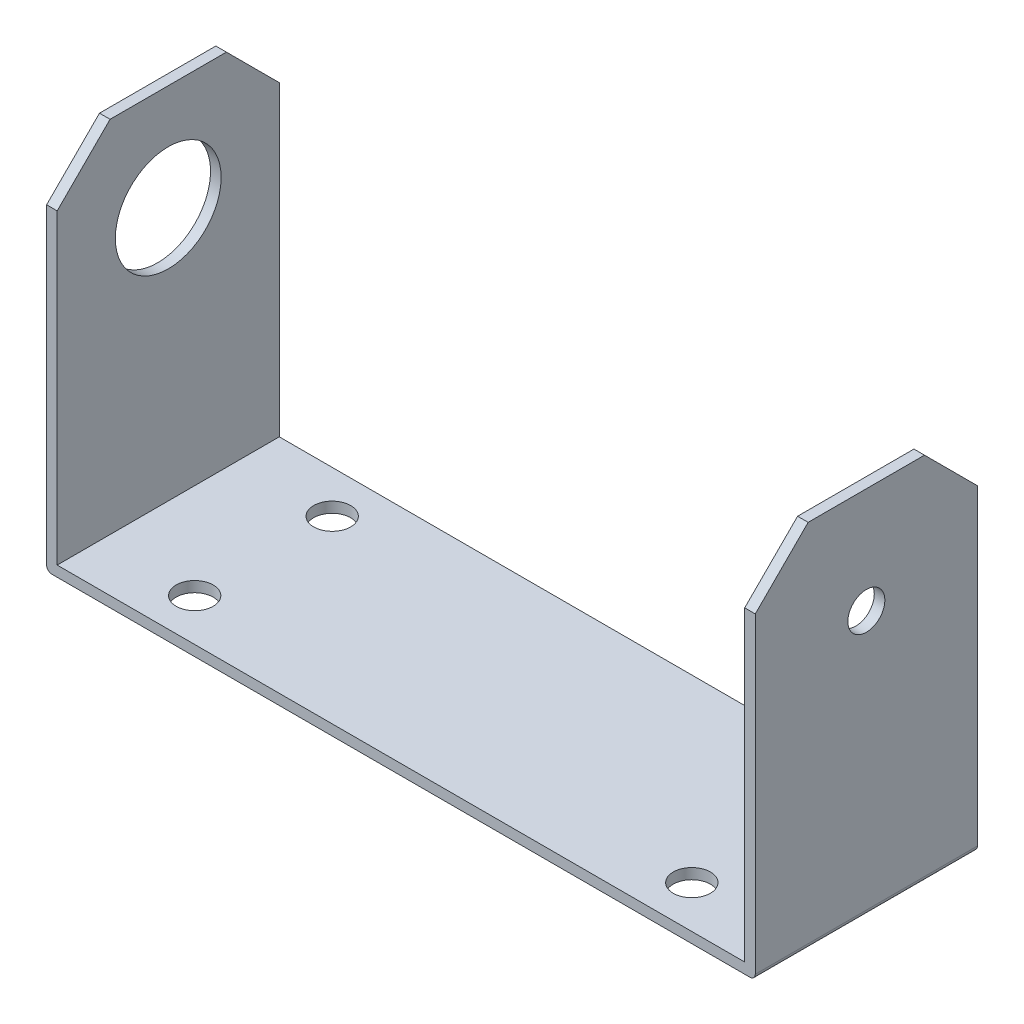
SolidWorks part; units mm, degrees
ref_plane "前视基准面" through (0, 0, 0) normal (0, 0, 1) x (1, 0, 0)
ref_plane "上视基准面" through (0, 0, 0) normal (0, 1, 0) x (1, 0, 0)
ref_plane "右视基准面" through (0, 0, 0) normal (1, 0, 0) x (0, 0, -1)
sketch "草图1" plane through (0, 0, 0) normal (0, 1, 0) x (1, 0, 0)
  line L0 (0, 0) -> (-67, 0)
  line L1 (-67, 0) -> (-67, 21)
  line L2 (-67, 21) -> (0, 21)
  line L3 (0, 21) -> (0, 0)
  dimension "D1" = 67
  dimension "D2" = 21
extrude "凸台-拉伸1" add sketch "草图1" along normal blind 35
shell "抽壳1" thickness 1
fillet "圆角2" radius 0.5 2 edges at (0, 0, -10.5) (-67, 0, -10.5)
chamfer "倒角1" distance 5 distance2 5 4 edges at (-0.5, 35, -21) (-0.5, 35, 0) (-66.5, 35, -21) (-66.5, 35, 0)
hole_wizard "Ø3.5 (3.5) 直径槽口1" positions "草图2" profile "草图4" size "Ø3.5" standard "GB" slot yes end condition through all
sketch "草图2" plane through (0, 1, 0) normal (0, 1, 0) x (1, 0, 0)
  line L0 (-1, 21) -> (-66, 21) construction
  line L1 (-66, 0) -> (-1, 0) construction
  line L2 (-33.5, 21) -> (-33.5, 0) construction
  point P0 (-57, 17)
  point P2 (-10, 17)
  point P4 (-10, 4)
  point P6 (-57, 4)
  dimension "D1" = 4
  dimension "D2" = 4
  dimension "D3" = 23.5
  dimension "D4" = 23.5
sketch "草图4" plane through (-57, 1, -17) normal (1, 0, 0) x (0, 0, 1)
  line L0 (0, 0) -> (0, 1)
  line L1 (0, 1) -> (1.75, 1)
  line L2 (1.75, 1) -> (1.75, 0)
  line L5 (1.75, 0) -> (0, 0)
  line L11 (0, -6.35) -> (0, 107.95) construction
  dimension "通孔孔直径" = 3.5
  dimension "通孔孔深度" = 1
hole_wizard "Ø10.0 (10) 直径槽口1" positions "草图5" profile "草图6" size "Ø10.0" standard "GB"
sketch "草图5" plane through (-67, 0, 0) normal (-1, 0, 0) x (0, 0, 1)
  line L0 (-16, 35) -> (-5, 35) construction
  line L1 (-21, 30) -> (-21, 0.5) construction
  point P12 (-10.5, 25)
  dimension "D1" = 10
  dimension "D2" = 10.5
sketch "草图6" plane through (-67, 25, -10.5) normal (0, 1, 0) x (0, 0, 1)
  line L0 (0, 0) -> (0, 1)
  line L1 (0, 1) -> (5, 1)
  line L2 (5, 1) -> (5, 0)
  line L5 (5, 0) -> (0, 0)
  line L11 (0, -6.35) -> (0, 107.95) construction
  dimension "通孔孔直径" = 10
  dimension "通孔孔深度" = 1
hole_wizard "Ø3.5 (3.5) 直径槽口2" positions "草图7" profile "草图8" size "Ø3.5" standard "GB" slot yes end condition up to next
sketch "草图7" plane through (0, 0, 0) normal (1, 0, 0) x (0, 0, -1)
  line L0 (5, 35) -> (16, 35) construction
  point P0 (10.5, 25)
  point P5 (0, 0)
  point P6 (10.5, 35)
  dimension "D1" = 10
sketch "草图8" plane through (0, 25, -10.5) normal (0, 1, 0) x (0, 0, -1)
  line L0 (0, 0) -> (0, 1)
  line L1 (0, 1) -> (1.75, 1)
  line L2 (1.75, 1) -> (1.75, 0)
  line L5 (1.75, 0) -> (0, 0)
  line L11 (0, -6.35) -> (0, 107.95) construction
  dimension "通孔孔直径" = 3.5
  dimension "通孔孔深度" = 1
